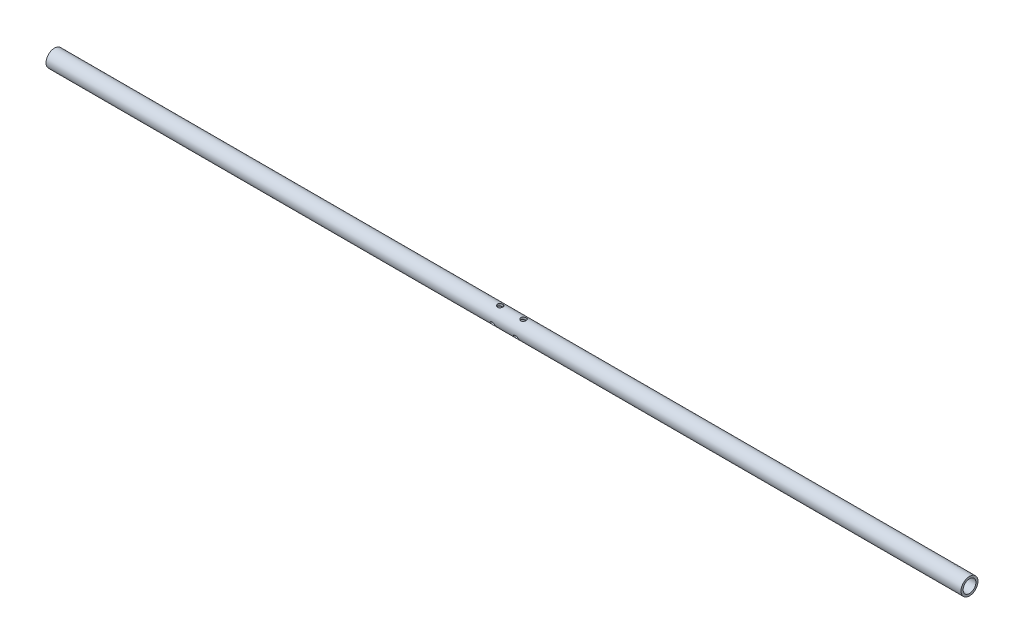
SolidWorks part; units mm, degrees
material "ASTM A36 Steel"
ref_plane "Front" through (0, 0, 0) normal (0, 0, 1) x (1, 0, 0)
ref_plane "Top" through (0, 0, 0) normal (0, 1, 0) x (1, 0, 0)
ref_plane "Right" through (0, 0, 0) normal (1, 0, 0) x (0, 0, -1)
sketch "Sketch1" plane through (0, 0, 0) normal (1, 0, 0) x (0, 0, -1)
  circle A0 centre (0, 0) radius 4
  dimension "D1" = 8
extrude "Extrude-Thin1" add sketch "Sketch1" along normal mid plane 431 thin thin type one direction reverse wall 1
hole_wizard "M3 Tapped Hole1" positions "Sketch4" profile "Sketch3" tap size "M3" standard "ISO"
sketch "Sketch4" plane through (0, 0, 0) normal (0, 1, 0) x (1, 0, 0)
  line L0 (0, 0) -> (0, 10.8998) construction
  point P0 (-5.5, 0)
  point P5 (5.5, 0)
  dimension "D1" = 11
sketch "Sketch3" plane through (-5.5, 0, 0) normal (1, 0, 0) x (0, 0, -1)
  line L0 (0, 0) -> (0, 5.4655)
  line L1 (0, 5.4655) -> (1.25, 5.4655)
  line L2 (1.25, 5.4655) -> (1.25, 0)
  line L5 (1.25, 0) -> (0, 0)
  line L11 (0, -6.35) -> (0, 107.95) construction
  dimension "Thru Tap Drill Dia." = 2.5
  dimension "Thru Tap Drill Depth" = 5.4655
cosmetic thread "Hole Thread1" parameters "D2"=3
cosmetic thread "Hole Thread2" parameters "D2"=3
pattern_circular "CirPattern1" count 3 over 360 about axis through (215.5, 0, 0) along (-1, 0, 0) of "M3 Tapped Hole1"
